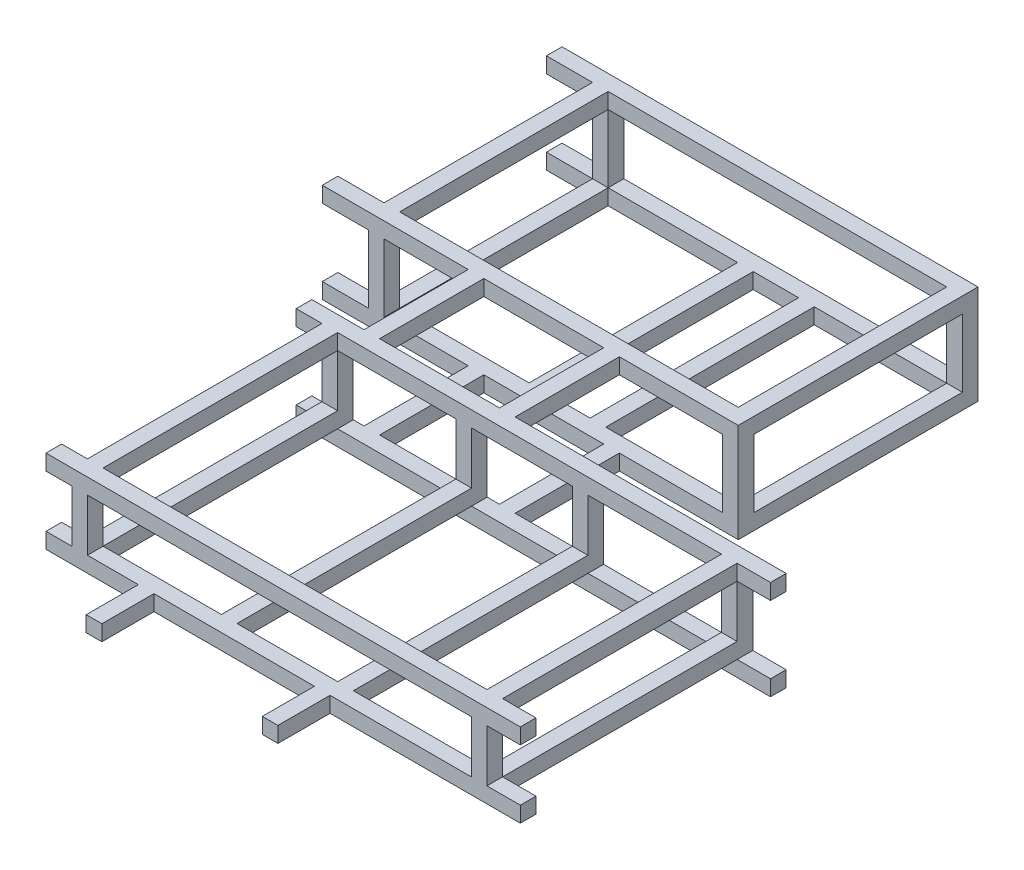
SolidWorks part; units mm, degrees
ref_plane "前视基准面" through (0, 0, 0) normal (0, 0, 1) x (1, 0, 0)
ref_plane "上视基准面" through (0, 0, 0) normal (0, 1, 0) x (1, 0, 0)
ref_plane "右视基准面" through (0, 0, 0) normal (1, 0, 0) x (0, 0, -1)
other "Configuration Table"
sketch "草图1" plane through (0, 0, 0) normal (0, 1, 0) x (1, 0, 0)
  line L1 (0, 0) -> (910, 0)
  line L2 (0, 0) -> (0, 30)
  line L3 (0, 30) -> (910, 30)
  line L4 (910, 0) -> (910, 30)
  line L5 (49.4184, 30) -> (79.4184, 30)
  line L6 (49.4184, 30) -> (49.4184, 480)
  line L7 (49.4184, 480) -> (79.4184, 480)
  line L8 (79.4184, 30) -> (79.4184, 480)
  line L9 (306.4085, 30) -> (336.4085, 30)
  line L10 (306.4085, 30) -> (306.4085, 480)
  line L11 (306.4085, 480) -> (336.4085, 480)
  line L12 (336.4085, 30) -> (336.4085, 480)
  line L13 (529.693, 30) -> (559.693, 30)
  line L14 (529.693, 30) -> (529.693, 480)
  line L15 (529.693, 480) -> (559.693, 480)
  line L16 (559.693, 30) -> (559.693, 480)
  line L17 (815.9337, 30) -> (845.9337, 30)
  line L18 (815.9337, 30) -> (815.9337, 480)
  line L19 (815.9337, 480) -> (845.9337, 480)
  line L20 (845.9337, 30) -> (845.9337, 480)
  line L21 (0, 510) -> (910, 510)
  line L22 (0, 510) -> (0, 480)
  line L23 (0, 480) -> (910, 480)
  line L24 (910, 510) -> (910, 480)
  dimension "D1" = 30
  dimension "D2" = 910
  dimension "D3" = 450
  dimension "D4" = 30
  dimension "D5" = 30
  dimension "D6" = 30
  dimension "D7" = 30
  dimension "D8" = 910
  dimension "D9" = 0
  dimension "D10" = 30
  dimension "D11" = 0
  dimension "D12" = 450
  dimension "D13" = 450
  dimension "D14" = 450
extrude "凸台-拉伸1" add sketch "草图1" along normal blind 30 contours L3 L8 L7 L6 | L1 L4 L3 L2 | L3 L12 L11 L10 | L3 L16 L15 L14 | L3 L20 L19 L18 | L24 L21 L22 L23 L7 L11 L15 L19
sketch "草图2" plane through (0, 30, 0) normal (0, 1, 0) x (1, 0, 0)
  line L0 (0, 0) -> (910, 0) construction
  line L1 (49.4184, 30) -> (79.5282, 30)
  line L2 (49.4184, 30) -> (49.4184, 0)
  line L3 (49.4184, 0) -> (79.5282, 0)
  line L4 (79.5282, 30) -> (79.5282, 0)
  line L5 (0, 510) -> (910, 510) construction
  line L6 (815.9337, 30) -> (845.9337, 30)
  line L7 (815.9337, 30) -> (815.9337, 0)
  line L8 (815.9337, 0) -> (845.9337, 0)
  line L9 (845.9337, 30) -> (845.9337, 0)
  line L10 (49.4184, 480) -> (79.4184, 480)
  line L11 (49.4184, 480) -> (49.4184, 510)
  line L12 (49.4184, 510) -> (79.4184, 510)
  line L13 (79.4184, 480) -> (79.4184, 510)
  line L15 (845.9337, 480) -> (815.9337, 480)
  line L16 (845.9337, 480) -> (845.9337, 510)
  line L17 (845.9337, 510) -> (815.9337, 510)
  line L18 (815.9337, 480) -> (815.9337, 510)
extrude "凸台-拉伸2" add sketch "草图2" along normal blind 100
sketch "草图3" plane through (0, 130, 0) normal (0, 1, 0) x (1, 0, 0)
  line L1 (0, 510) -> (910, 510)
  line L2 (0, 510) -> (0, 480)
  line L3 (0, 480) -> (910, 480)
  line L4 (910, 510) -> (910, 480)
  line L5 (910, 0) -> (0, 0)
  line L6 (910, 0) -> (910, 30)
  line L7 (910, 30) -> (0, 30)
  line L8 (0, 0) -> (0, 30)
  line L9 (49.4184, 480) -> (79.5282, 480)
  line L10 (49.4184, 480) -> (49.4184, 30)
  line L11 (49.4184, 30) -> (79.5282, 30)
  line L12 (79.5282, 480) -> (79.5282, 30)
  line L13 (815.9337, 480) -> (845.9337, 480)
  line L14 (815.9337, 480) -> (815.9337, 30)
  line L15 (815.9337, 30) -> (845.9337, 30)
  line L16 (845.9337, 480) -> (845.9337, 30)
  line M9 (49.4184, 510) -> (49.4184, 480)
  line M10 (49.4184, 480) -> (79.4184, 480)
  line M11 (79.4184, 480) -> (79.4184, 510)
  line M12 (79.4184, 510) -> (49.4184, 510)
extrude "凸台-拉伸3" add sketch "草图3" along normal blind 30 contours L4 L1 L3 M11 | L2 L3 L1 M9 | M12 M9 M10 M11 | L8 L5 L6 L7 | L12 L3 L10 L7 M10 | L16 L3 L14 L7
sketch "草图4" plane through (0, 160, 0) normal (0, 1, 0) x (1, 0, 0)
  line L0 (0, 510) -> (0, 480) construction
  line L1 (-180, 740) -> (670, 740)
  line L2 (-180, 740) -> (-180, 710)
  line L3 (-180, 710) -> (670, 710)
  line L4 (670, 740) -> (670, 710)
  line L5 (0, 510) -> (910, 510) construction
  line L7 (-180, 1170) -> (670, 1170)
  line L8 (-180, 1170) -> (-180, 1140)
  line L9 (-180, 1140) -> (670, 1140)
  line L10 (670, 1170) -> (670, 1140)
  line L11 (-91.5208, 1140) -> (-61.5208, 1140)
  line L12 (-91.5208, 1140) -> (-91.5208, 740)
  line L13 (-91.5208, 740) -> (-61.5208, 740)
  line L14 (-61.5208, 1140) -> (-61.5208, 740)
  line L15 (588.0274, 1140) -> (618.0274, 1140)
  line L16 (588.0274, 1140) -> (588.0274, 740)
  line L17 (588.0274, 740) -> (618.0274, 740)
  line L18 (618.0274, 1140) -> (618.0274, 740)
  point P6 (0, 495)
  dimension "D1" = 850
  dimension "D2" = 180
  dimension "D3" = 200
  dimension "D4" = 30
  dimension "D5" = 30
  dimension "D6" = 400
  dimension "D7" = 30
  dimension "D8" = 30
  dimension "D9" = 0
extrude "凸台-拉伸4" add sketch "草图4" against normal blind 30 separate body contours L10 L7 L8 L9 | L14 L9 L12 L1 | L18 L17 L16 L15
sketch "草图5" plane through (0, 130, 0) normal (0, -1, 0) x (-1, 0, 0)
  line L0 (180, 710) -> (-670, 710) construction
  line L1 (91.5208, 740) -> (61.5208, 740)
  line L2 (91.5208, 740) -> (91.5208, 710)
  line L3 (91.5208, 710) -> (61.5208, 710)
  line L4 (61.5208, 740) -> (61.5208, 710)
  line L5 (180, 1170) -> (-670, 1170) construction
  line L6 (-588.0274, 740) -> (-618.0274, 740)
  line L7 (-588.0274, 740) -> (-588.0274, 710)
  line L8 (-588.0274, 710) -> (-618.0274, 710)
  line L9 (-618.0274, 740) -> (-618.0274, 710)
  line L10 (-588.0274, 1140) -> (-618.0274, 1140)
  line L11 (-588.0274, 1140) -> (-588.0274, 1170)
  line L12 (-588.0274, 1170) -> (-618.0274, 1170)
  line L13 (-618.0274, 1140) -> (-618.0274, 1170)
  line L15 (91.5208, 1140) -> (61.5208, 1140)
  line L16 (91.5208, 1140) -> (91.5208, 1170)
  line L17 (91.5208, 1170) -> (61.5208, 1170)
  line L18 (61.5208, 1140) -> (61.5208, 1170)
extrude "凸台-拉伸5" add sketch "草图5" along normal blind 130
sketch "草图6" plane through (0, 0, 0) normal (0, -1, 0) x (-1, 0, 0)
  line L1 (180, 710) -> (-670, 710)
  line L2 (180, 710) -> (180, 740)
  line L3 (180, 740) -> (-670, 740)
  line L4 (-670, 710) -> (-670, 740)
  line L5 (-670, 1170) -> (180, 1170)
  line L6 (-670, 1170) -> (-670, 1140)
  line L7 (-670, 1140) -> (180, 1140)
  line L8 (180, 1170) -> (180, 1140)
  line L9 (91.5208, 740) -> (61.5208, 740)
  line L10 (91.5208, 740) -> (91.5208, 1140)
  line L11 (91.5208, 1140) -> (61.5208, 1140)
  line L12 (61.5208, 740) -> (61.5208, 1140)
  line L13 (-588.0274, 740) -> (-618.0274, 740)
  line L14 (-588.0274, 740) -> (-588.0274, 1140)
  line L15 (-588.0274, 1140) -> (-618.0274, 1140)
  line L16 (-618.0274, 740) -> (-618.0274, 1140)
  line L17 (-186.8226, 740) -> (-216.8226, 740)
  line L18 (-186.8226, 740) -> (-186.8226, 1140)
  line L19 (-186.8226, 1140) -> (-216.8226, 1140)
  line L20 (-216.8226, 740) -> (-216.8226, 1140)
  line L21 (-303.8613, 740) -> (-333.8613, 740)
  line L22 (-303.8613, 740) -> (-303.8613, 1140)
  line L23 (-303.8613, 1140) -> (-333.8613, 1140)
  line L24 (-333.8613, 740) -> (-333.8613, 1140)
  point P32 (0, 0)
  point P33 (0, 0)
  line M5 (91.5208, 710) -> (91.5208, 740)
  line M6 (91.5208, 740) -> (61.5208, 740)
  line M7 (61.5208, 740) -> (61.5208, 710)
  line M8 (61.5208, 710) -> (91.5208, 710)
  dimension "D1" = 30
  dimension "D2" = 30
  dimension "D3" = 0
extrude "凸台-拉伸6" add sketch "草图6" along normal blind 30 contours L4 L1 L3 M7 | L2 L3 L1 M5 | M8 M5 M6 M7 | L12 L10 L7 M6 | L20 L3 L18 L7 | L24 L3 L22 L7 | L16 L3 L14 L7 | L8 L5 L6 L7
sketch "草图8" plane through (0, 0, -510) normal (0, 0, -1) x (-1, 0, 0)
  line L0 (-588.0274, 0) -> (61.5208, 0) construction
  line L1 (-815.9337, 30) -> (-79.4184, 30)
  line L2 (-815.9337, 30) -> (-815.9337, 0)
  line L3 (-815.9337, 0) -> (-79.4184, 0)
  line L4 (-79.4184, 30) -> (-79.4184, 0)
  line L5 (0, 0) -> (-910, 0) construction
  line L6 (-910, 30) -> (-845.9337, 30)
  line L7 (-910, 30) -> (-910, 0)
  line L8 (-910, 0) -> (-845.9337, 0)
  line L9 (-845.9337, 30) -> (-845.9337, 0)
  line L10 (0, 30) -> (-49.4184, 30)
  line L11 (0, 30) -> (0, 0)
  line L12 (0, 0) -> (-49.4184, 0)
  line L13 (-49.4184, 30) -> (-49.4184, 0)
extrude "切除-拉伸2" cut sketch "草图8" against normal blind 30
sketch "草图9" plane through (0, -30, 0) normal (0, -1, 0) x (-1, 0, 0)
  line L1 (0, 480) -> (-910, 480)
  line L2 (0, 480) -> (0, 510)
  line L3 (0, 510) -> (-910, 510)
  line L4 (-910, 480) -> (-910, 510)
extrude "凸台-拉伸7" add sketch "草图9" against normal blind 30 separate body
sketch "草图12" plane through (0, 0, -510) normal (0, 0, -1) x (-1, 0, 0)
  line L0 (0, 0) -> (-910, 0) construction
  line L5 (-79.4184, 130) -> (-815.9337, 130) construction
  line L6 (-559.693, 0) -> (-529.693, 0)
  line L7 (-559.693, 0) -> (-559.693, 130)
  line L8 (-559.693, 130) -> (-529.693, 130)
  line L9 (-529.693, 0) -> (-529.693, 130)
  line L10 (-588.0274, 0) -> (61.5208, 0) construction
  line L11 (-336.4085, 0) -> (-306.4085, 0)
  line L12 (-336.4085, 0) -> (-336.4085, 130)
  line L13 (-336.4085, 130) -> (-306.4085, 130)
  line L14 (-306.4085, 0) -> (-306.4085, 130)
  dimension "D2" = 0
  dimension "D3" = 0
extrude "凸台-拉伸8" add sketch "草图12" against normal blind 30
sketch "草图13" plane through (0, -30, 0) normal (0, -1, 0) x (-1, 0, 0)
  line L0 (0, 510) -> (-910, 510) construction
  line L1 (-100, 510) -> (-130, 510)
  line L2 (-100, 510) -> (-100, 710)
  line L3 (-100, 710) -> (-130, 710)
  line L4 (-130, 510) -> (-130, 710)
  line L5 (180, 710) -> (-670, 710) construction
  line L6 (-670, 710) -> (-670, 740) construction
  line L7 (-360, 510) -> (-390, 510)
  line L8 (-360, 510) -> (-360, 710)
  line L9 (-360, 710) -> (-390, 710)
  line L10 (-390, 510) -> (-390, 710)
  line L11 (0, 480) -> (0, 510) construction
  point P16 (0, 495)
  dimension "D1" = 30
  dimension "D2" = 30
  dimension "D3" = 280
  dimension "D4" = 100
extrude "凸台-拉伸9" add sketch "草图13" against normal blind 30
sketch "草图14" plane through (0, 160, 0) normal (0, 1, 0) x (1, 0, 0)
  line L1 (100, 710) -> (130, 710)
  line L2 (100, 710) -> (100, 510)
  line L3 (100, 510) -> (130, 510)
  line L4 (130, 710) -> (130, 510)
  line L5 (360, 710) -> (390, 710)
  line L6 (360, 710) -> (360, 510)
  line L7 (360, 510) -> (390, 510)
  line L8 (390, 710) -> (390, 510)
  dimension "D1" = 30
extrude "凸台-拉伸10" add sketch "草图14" against normal blind 30
sketch "草图15" plane through (670, 0, 0) normal (1, 0, 0) x (0, 0, -1)
  line L1 (703.6493, 183.5593) -> (1193.1812, 183.5593)
  line L2 (703.6493, 183.5593) -> (703.6493, -71.1633)
  line L3 (703.6493, -71.1633) -> (1193.1812, -71.1633)
  line L4 (1193.1812, 183.5593) -> (1193.1812, -71.1633)
extrude "切除-拉伸3" cut sketch "草图15" against normal up to surface (51.9726 mm away) up to face at (618.0274, 145, -940)
sketch "草图16" plane through (0, 0, 0) normal (0, 0, 1) x (1, 0, 0)
  line L0 (79.5282, 30) -> (815.9337, 30) construction
  line L1 (177.1652, 30) -> (207.1652, 30)
  line L2 (177.1652, 30) -> (177.1652, 0)
  line L3 (177.1652, 0) -> (207.1652, 0)
  line L4 (207.1652, 30) -> (207.1652, 0)
  line L5 (0, 0) -> (910, 0) construction
  line L7 (514.9586, 30) -> (544.9586, 30)
  line L8 (514.9586, 30) -> (514.9586, 0)
  line L9 (514.9586, 0) -> (544.9586, 0)
  line L10 (544.9586, 30) -> (544.9586, 0)
  dimension "D1" = 30
  dimension "D2" = 30
extrude "凸台-拉伸11" add sketch "草图16" along normal blind 100
equation "\"D12@草图1\"=\"D3@草图1\""
equation "\"D13@草图1\"=\"D3@草图1\""
equation "\"D14@草图1\"=\"D3@草图1\""
